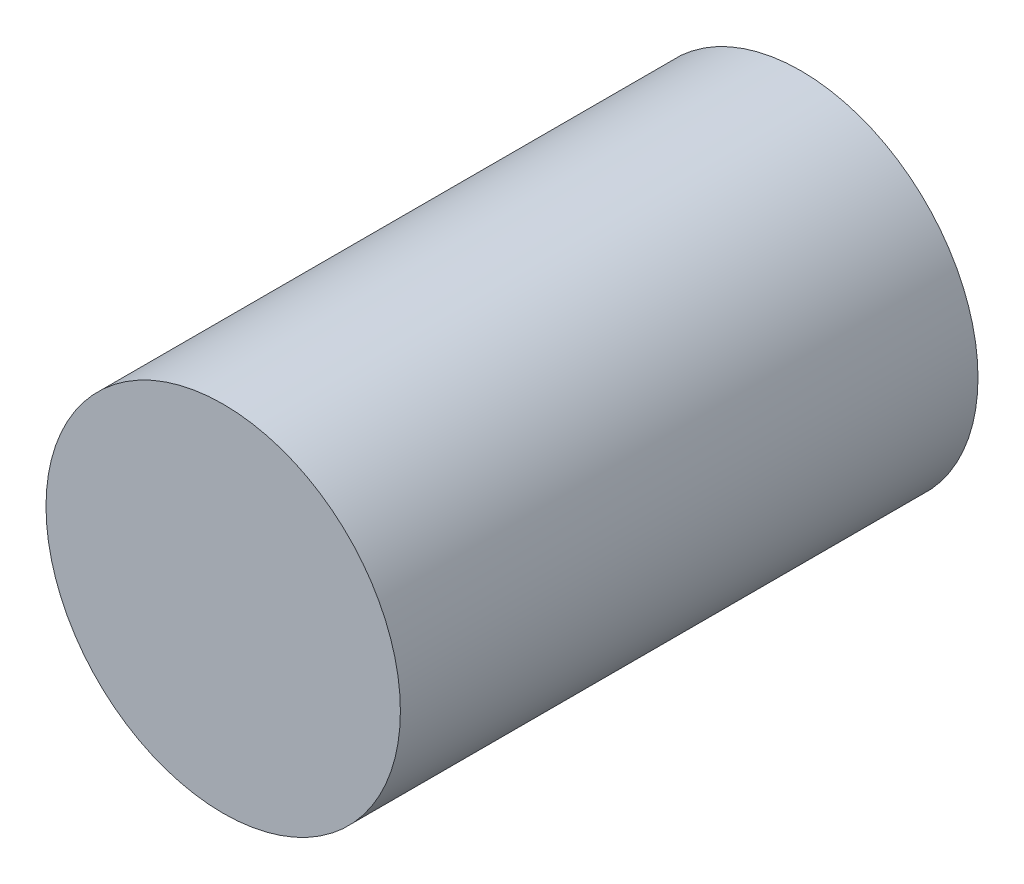
SolidWorks part; units mm, degrees
ref_plane "Front" through (0, 0, 0) normal (0, 0, 1) x (1, 0, 0)
ref_plane "Top" through (0, 0, 0) normal (0, 1, 0) x (1, 0, 0)
ref_plane "Right" through (0, 0, 0) normal (1, 0, 0) x (0, 0, -1)
sketch "Sketch1" plane through (0, 0, 0) normal (0, 0, 1) x (1, 0, 0)
  circle A0 centre (0, 0) radius 23.377
extrude "Extrude1" add sketch "Sketch1" along normal blind 76.2
